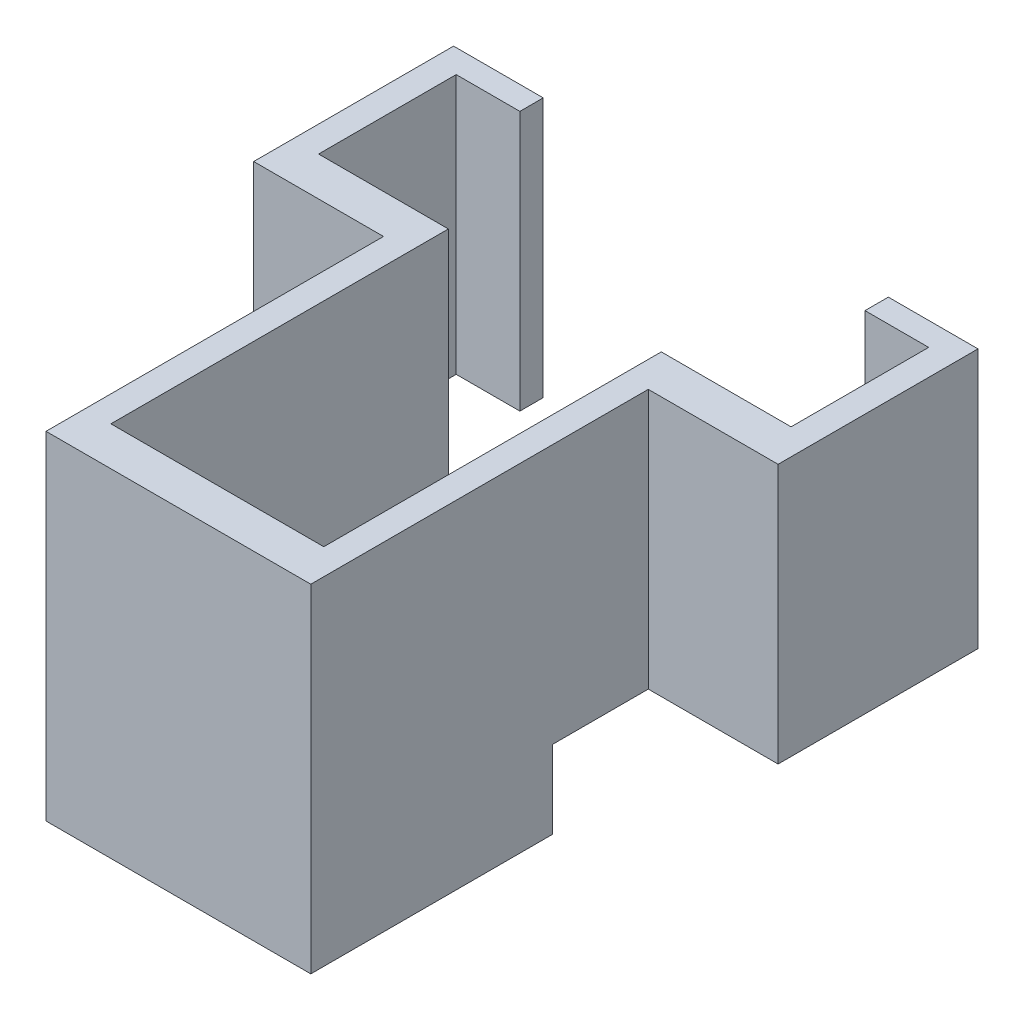
SolidWorks part; units mm, degrees
ref_plane "Front Plane" through (0, 0, 0) normal (0, 0, 1) x (1, 0, 0)
ref_plane "Top Plane" through (0, 0, 0) normal (0, 1, 0) x (1, 0, 0)
ref_plane "Right Plane" through (0, 0, 0) normal (1, 0, 0) x (0, 0, -1)
sketch "Sketch1" plane through (0, 0, 0) normal (0, 1, 0) x (1, 0, 0)
  line L6 (2.4534, -5.3) -> (-2.5466, -5.3)
  line L11 (-2.5466, -5.3) -> (-2.5466, -18.3)
  line L12 (-2.5466, -18.3) -> (-10.7466, -18.3)
  line L13 (-10.7466, -18.3) -> (-10.7466, -5.3)
  line L14 (-10.7466, -5.3) -> (-15.7466, -5.3)
  line L17 (0, 0) -> (0, 0.9)
  line L19 (-16.7466, 0.9) -> (-16.7466, -6.8)
  line L21 (-16.7466, -6.8) -> (-11.7466, -6.8)
  line L22 (-11.7466, -6.8) -> (-11.7466, -19.8)
  line L23 (-11.7466, -19.8) -> (-1.5466, -19.8)
  line L24 (-1.5466, -19.8) -> (-1.5466, -6.8)
  line L25 (-1.5466, -6.8) -> (3.4534, -6.8)
  line L26 (3.4534, -6.8) -> (3.4534, 0.9)
  line L28 (-13.2931, 0.9) -> (-13.2931, 0)
  line L29 (2.4534, -5.3) -> (2.4534, 0)
  line L30 (-15.7466, 0) -> (-15.7466, -5.3)
  line L31 (3.4534, 0.9) -> (0, 0.9)
  line L32 (2.4534, 0) -> (0, 0)
  line L33 (-13.2931, 0.9) -> (-16.7466, 0.9)
  line L34 (-13.2931, 0) -> (-15.7466, 0)
  dimension "D1" = 8.2
  dimension "D2" = 5.3
  dimension "D3" = 1.5
  dimension "D4" = 1
  dimension "D5" = 1
  dimension "D6" = 0.9
  dimension "D7" = 11.5
  dimension "D8" = 1
  dimension "D9" = 18.2
  dimension "D10" = 1.5
extrude "Boss-Extrude1" add sketch "Sketch1" along normal blind 13
sketch "Sketch2" plane through (-16.7466, 0, 0) normal (-1, 0, 0) x (0, 0, 1)
  line L1 (-0.9, 0) -> (10.4859, 0)
  line L2 (-0.9, 0) -> (-0.9, 3)
  line L3 (-0.9, 3) -> (10.4859, 3)
  line L4 (10.4859, 0) -> (10.4859, 3)
  dimension "D1" = 3
extrude "Cut-Extrude1" cut sketch "Sketch2" against normal through all both and the other way through all
